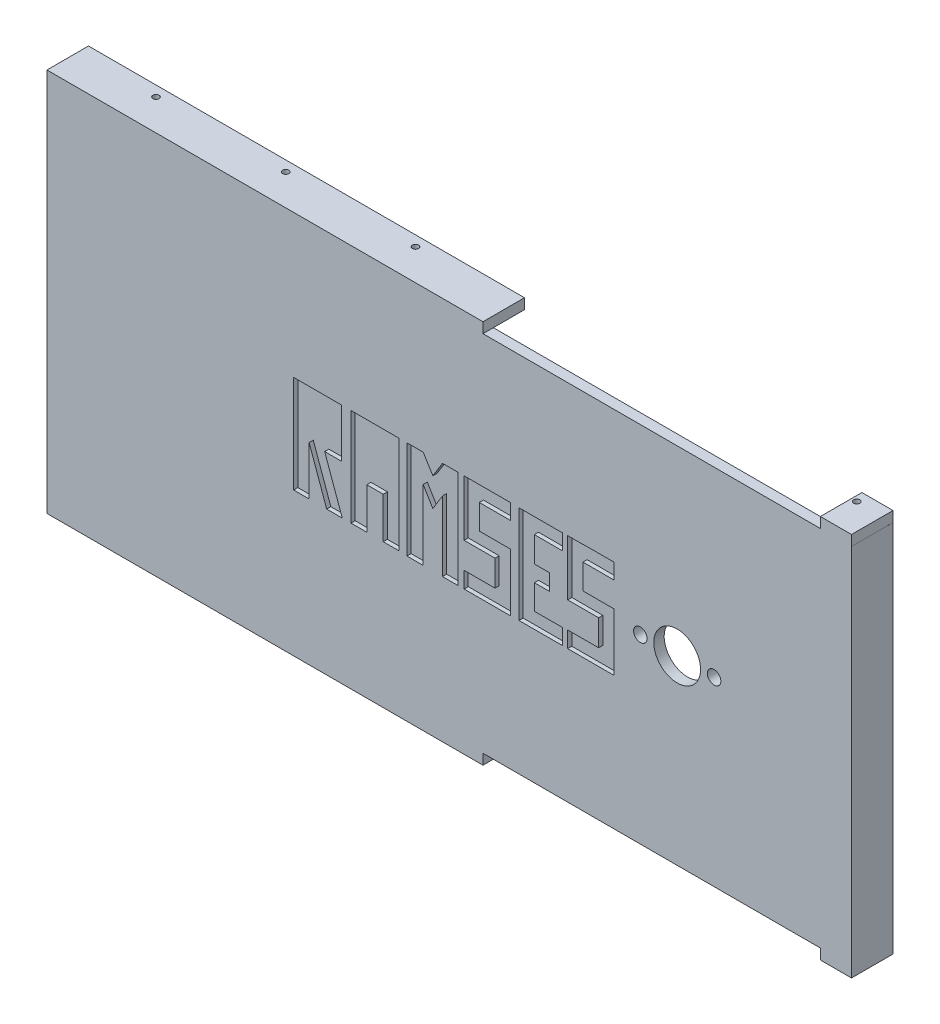
SolidWorks part; units mm, degrees
ref_plane "Front Plane" through (0, 0, 0) normal (0, 0, 1) x (1, 0, 0)
ref_plane "Top Plane" through (0, 0, 0) normal (0, 1, 0) x (1, 0, 0)
ref_plane "Right Plane" through (0, 0, 0) normal (1, 0, 0) x (0, 0, -1)
sketch "Sketch1" plane through (0, 0, 0) normal (0, 0, 1) x (1, 0, 0)
  line L1 (-191.77, 114.3) -> (191.77, 114.3)
  line L2 (-191.77, 114.3) -> (-191.77, -114.3)
  line L3 (-191.77, -114.3) -> (191.77, -114.3)
  line L4 (191.77, 114.3) -> (191.77, -114.3)
  line L5 (-191.77, 114.3) -> (191.77, -114.3) construction
  line L6 (-191.77, -114.3) -> (191.77, 114.3) construction
  point P1 (0, 0)
  dimension "D1" = 383.54
  dimension "D2" = 228.6
extrude "Boss-Extrude1" add sketch "Sketch1" along normal blind 5.08
ref_plane "Plane1" through (0, 0, 5.08) normal (0, 0, 1) x (1, 0, 0)
sketch "Sketch3" plane through (0, 0, 5.08) normal (0, 0, 1) x (1, 0, 0)
  line L0 (-20.7021, -23.9948) -> (-20.7021, 23.9948) construction
  line L5 (-76.1221, 23.9948) -> (76.1221, 23.9948)
  line L6 (-76.1221, 23.9948) -> (-76.1221, -23.9948)
  line L7 (-76.1221, -23.9948) -> (76.1221, -23.9948)
  line L8 (76.1221, 23.9948) -> (76.1221, -23.9948)
  line L9 (-76.1221, 23.9948) -> (76.1221, -23.9948) construction
  line L10 (-76.1221, -23.9948) -> (76.1221, 23.9948) construction
  line L17 (-20.7021, 23.9948) -> (4.3607, 23.9948) construction
  line L18 (4.3607, 23.9948) -> (4.3607, -23.9948) construction
  line L19 (4.3607, -23.9948) -> (29.9215, -23.9948) construction
  line L20 (29.9215, -23.9948) -> (29.9215, 23.9948) construction
  line L21 (-12.7351, 23.9948) -> (-8.0047, 16.3708)
  line L22 (-20.7021, 23.9948) -> (-12.7351, 23.9948)
  line L23 (-20.7021, 23.9948) -> (-20.7021, -23.9948)
  line L24 (-20.7021, -23.9948) -> (-12.7351, -23.9948)
  line L50 (-12.7351, 23.9948) -> (-12.7351, -23.9948)
  line L51 (4.3607, 23.9948) -> (-3.2743, 23.9948)
  line L64 (4.3607, 23.9948) -> (4.3607, -23.9948)
  line L65 (4.3607, -23.9948) -> (-3.2743, -23.9948)
  line L114 (-3.2743, 23.9948) -> (-3.2743, -23.9948)
  line L115 (-8.0047, 16.3708) -> (-3.2743, 23.9948)
  line L153 (-8.0047, 2.4263) -> (-3.2743, 10.2085)
  line L154 (-8.0047, 2.4263) -> (-12.7351, 10.3134)
  line L155 (-12.7351, 23.9948) -> (-3.2743, 23.9948) construction
  line L156 (-76.163, 24.0432) -> (-76.163, -23.7288) construction
  line L157 (-68.5707, 0.1572) -> (-60.9507, 0.1572)
  line L158 (-76.163, 24.0432) -> (-68.5707, 24.0432)
  line L159 (-76.163, 24.0432) -> (-76.163, -23.7288)
  line L160 (-76.163, -23.7288) -> (-68.5707, -23.7288)
  line L161 (-68.5707, 24.0432) -> (-68.5707, -23.7288)
  line L162 (-76.163, 24.0432) -> (-52.7715, 24.0432)
  line L163 (-76.163, 24.0432) -> (-76.163, 16.3708)
  line L164 (-76.163, 16.3708) -> (-52.7715, 16.3708)
  line L165 (-52.7715, 24.0432) -> (-52.7715, 16.3708)
  line L166 (-52.7715, 24.0432) -> (-60.1444, 24.0432)
  line L167 (-52.7715, 24.0432) -> (-52.7715, 7.9935)
  line L168 (-52.7715, 7.9935) -> (-60.1444, 7.9935)
  line L169 (-60.1444, 24.0432) -> (-60.1444, 7.9935)
  line L170 (-52.7715, 7.9935) -> (-76.163, 7.9935)
  line L171 (-52.7715, 7.9935) -> (-52.7715, 0.1572)
  line L172 (-52.7715, 0.1572) -> (-76.163, 0.1572)
  line L173 (-76.163, 7.9935) -> (-76.163, 0.1572)
  line L174 (-68.5707, 0.1572) -> (-59.9689, -23.7288)
  line L175 (-60.9507, 0.1572) -> (-52.3489, -23.7288)
  line L176 (-59.9689, -23.7288) -> (-52.3489, -23.7288)
  line L177 (-24.6254, 24.0432) -> (-24.6254, -23.7288)
  line L178 (-24.6254, 0.1572) -> (-24.6254, 24.0432)
  line L179 (-48.0899, -23.7288) -> (-48.0899, 24.0432) construction
  line L180 (-48.0899, 24.0432) -> (-40.3512, 24.0432)
  line L181 (-48.0899, 24.0432) -> (-48.0899, -23.7288)
  line L182 (-48.0899, -23.7288) -> (-40.3512, -23.7288)
  line L183 (-40.3512, 24.0432) -> (-40.3512, -23.7288)
  line L184 (-48.0899, 24.0432) -> (-24.6254, 24.0432)
  line L185 (-48.0899, 24.0432) -> (-48.0899, 16.3708)
  line L186 (-48.0899, 16.3708) -> (-24.6254, 16.3708)
  line L187 (-24.6254, 24.0432) -> (-24.6254, 16.3708)
  line L188 (-24.6254, 24.0432) -> (-32.2936, 24.0432)
  line L189 (-24.6254, 24.0432) -> (-24.6254, -23.7288)
  line L190 (-24.6254, -23.7288) -> (-32.2936, -23.7288)
  line L191 (-32.2936, 24.0432) -> (-32.2936, -23.7288)
  line L192 (-48.0899, 4.232) -> (-24.6254, 4.232)
  line L193 (-48.0899, 4.232) -> (-48.0899, -3.5926)
  line L194 (-48.0899, -3.5926) -> (-24.6254, -3.5926)
  line L195 (-24.6254, 4.232) -> (-24.6254, -3.5926)
  line L196 (34.1269, -23.8878) -> (34.1269, 23.8842) construction
  line L197 (34.1269, 23.8842) -> (41.6289, 23.8842)
  line L198 (34.1269, 23.8842) -> (34.1269, -23.8878)
  line L199 (34.1269, -23.8878) -> (41.6289, -23.8878)
  line L200 (41.6289, 23.8842) -> (41.6289, -23.8878)
  line L201 (34.1269, -23.8878) -> (55.4971, -23.8878)
  line L202 (34.1269, -23.8878) -> (34.1269, -16.2154)
  line L203 (34.1269, -16.2154) -> (55.4971, -16.2154)
  line L204 (55.4971, -23.8878) -> (55.4971, -16.2154)
  line L205 (34.1269, 23.8842) -> (55.4971, 23.8842)
  line L206 (34.1269, 23.8842) -> (34.1269, 16.2607)
  line L207 (34.1269, 16.2607) -> (55.4971, 16.2607)
  line L208 (55.4971, 23.8842) -> (55.4971, 16.2607)
  line L209 (34.1489, 3.8067) -> (49.109, 3.8067)
  line L210 (34.1489, 3.8067) -> (34.1489, -4.1154)
  line L211 (34.1489, -4.1154) -> (49.109, -4.1154)
  line L212 (49.109, 3.8067) -> (49.109, -4.1154)
  line L213 (34.1489, 3.8067) -> (49.109, -4.1154) construction
  line L214 (34.1489, -4.1154) -> (49.109, 3.8067) construction
  line L215 (-8.0047, 23.9948) -> (-8.0047, 3.39) construction
  line L216 (80.6118, -23.9098) -> (80.6118, 24.0798) construction
  line L217 (7.2667, 23.9948) -> (29.9215, 23.9948)
  line L218 (7.2667, 23.9948) -> (7.2667, 16.4151)
  line L219 (7.2667, 16.4151) -> (29.9215, 16.4151)
  line L220 (29.9215, 23.9948) -> (29.9215, 16.4151)
  line L221 (7.2667, 23.9948) -> (14.7134, 23.9948)
  line L222 (7.2667, 23.9948) -> (7.2667, -3.3398)
  line L223 (7.2667, -3.3398) -> (14.7134, -3.3398)
  line L224 (14.7134, 23.9948) -> (14.7134, -3.3398)
  line L225 (7.2667, -3.3398) -> (29.9215, -3.3398)
  line L226 (7.2667, -3.3398) -> (7.2667, 4.2802)
  line L227 (7.2667, 4.2802) -> (29.9215, 4.2802)
  line L228 (29.9215, -3.3398) -> (29.9215, 4.2802)
  line L229 (29.9215, 4.2802) -> (22.4125, 4.2802)
  line L230 (29.9215, 4.2802) -> (29.9215, -23.9948)
  line L231 (29.9215, -23.9948) -> (22.4125, -23.9948)
  line L232 (22.4125, 4.2802) -> (22.4125, -23.9948)
  line L233 (29.9215, -23.9948) -> (7.2667, -23.9948)
  line L234 (29.9215, -23.9948) -> (29.9215, -16.061)
  line L235 (29.9215, -16.061) -> (7.2667, -16.061)
  line L236 (7.2667, -23.9948) -> (7.2667, -16.061)
  line L237 (57.9571, 24.0798) -> (80.6118, 24.0798)
  line L238 (57.9571, 24.0798) -> (57.9571, 16.5001)
  line L239 (57.9571, 16.5001) -> (80.6118, 16.5001)
  line L240 (80.6118, 24.0798) -> (80.6118, 16.5001)
  line L241 (57.9571, 24.0798) -> (65.4037, 24.0798)
  line L242 (57.9571, 24.0798) -> (57.9571, -3.2485)
  line L243 (57.9571, -3.2485) -> (65.4037, -3.2485)
  line L244 (65.4037, 24.0798) -> (65.4037, -3.2485)
  line L245 (57.9571, -3.2485) -> (80.6118, -3.2485)
  line L246 (57.9571, -3.2485) -> (57.9571, 4.2802)
  line L247 (57.9571, 4.2802) -> (80.6118, 4.2802)
  line L248 (80.6118, -3.2485) -> (80.6118, 4.2802)
  line L249 (80.6118, 4.2802) -> (73.1028, 4.2802)
  line L250 (80.6118, 4.2802) -> (80.6118, -23.9098)
  line L251 (80.6118, -23.9098) -> (73.1028, -23.9098)
  line L252 (73.1028, 4.2802) -> (73.1028, -23.9098)
  line L253 (80.6118, -23.9098) -> (57.9571, -23.9098)
  line L254 (80.6118, -23.9098) -> (80.6118, -15.976)
  line L255 (80.6118, -15.976) -> (57.9571, -15.976)
  line L256 (57.9571, -23.9098) -> (57.9571, -15.976)
  point P0 (0, 0)
  point P157 (41.6289, -0.1544)
  dimension "D1" = 47.7719
  dimension "D2" = 7.62
  dimension "D3" = 7.9338
extrude "Cut-Extrude4" cut sketch "Sketch3" against normal blind 2.032 and the other way blind 2.54 contours L6 L164 L161 L5 | L169 L5 L161 L164 | L5 L169 L164 L165 | L164 L169 L168 L167 | L172 L161 L170 L6 | L161 L172 L6 L160 | L170 L161 L164 L6 | L170 L169 L164 L161 | L172 L171 L168 L170 L161 L157 | L174 L176 L175 L157 | L181 L186 L183 L5 | L191 L5 L183 L186 | L5 L191 L186 L177 | L191 L192 L178 L186 | L183 L192 L191 L186 | L181 L192 L183 L186 | L181 L194 L183 L192 | L183 L194 L191 L192 | L191 L194 L177 L189 L192 | L194 L181 L182 L183 | L194 L191 L190 L189 | L50 L5 L23 L7 | L154 L153 L114 L115 L21 L50 | L5 L114 L7 L64 | L217 L224 L219 L220 | L224 L5 L218 L219 | L208 L205 L200 L207 | L222 L227 L224 L219 | L227 L222 L223 L224 | L232 L227 L224 L225 | L227 L232 L225 L228 | L235 L230 L225 L232 | L230 L235 L232 L7 | L236 L7 L232 L235 | L198 L207 L200 L197 | L211 L210 L209 L200 L207 L198 L203 | L210 L211 L200 L209 | L212 L209 L200 L211 | L203 L198 L199 L200 | L201 L204 L203 L200 | L242 L247 L244 L239 | L244 L5 L238 L239 | L5 L244 L239 L8 | L237 L244 L5 L8 L239 L240 | L247 L242 L243 L244 | L256 L253 L252 L255 | L252 L247 L244 L245 | L247 L252 L245 L8 | L245 L248 L247 L8 | L255 L250 L245 L8 | L255 L8 L245 L252 | L8 L255 L252 L251 | L250 L255 L8 L251
sketch "Sketch4" plane through (0, 0, 5.08) normal (0, 0, 1) x (1, 0, 0)
  line L0 (-191.77, 0) -> (191.77, 0) construction
  line L1 (-191.77, 114.3) -> (-191.77, -114.3) construction
  line L2 (191.77, -114.3) -> (191.77, 114.3) construction
  line L3 (191.77, 0) -> (191.77, 88.8363) construction
  line L4 (191.77, 88.8363) -> (191.77, -88.9637) construction
  line L5 (191.77, -88.9637) -> (-191.77, -88.9637) construction
  line L6 (-191.77, -88.9637) -> (-191.77, 88.8363) construction
  line L7 (-191.77, 88.8363) -> (191.77, 88.8363) construction
  line L9 (-191.77, 114.3) -> (191.77, 114.3)
  line L10 (-191.77, 114.3) -> (-191.77, 88.8363)
  line L11 (-191.77, 88.8363) -> (191.77, 88.8363)
  line L12 (191.77, 114.3) -> (191.77, 88.8363)
  line L13 (-191.77, -88.9637) -> (191.77, -88.9637)
  line L14 (-191.77, -88.9637) -> (-191.77, -114.3)
  line L15 (-191.77, -114.3) -> (191.77, -114.3)
  line L16 (191.77, -88.9637) -> (191.77, -114.3)
extrude "Cut-Extrude5" cut sketch "Sketch4" against normal blind 6.35
sketch "Sketch7" plane through (0, 0, 5.08) normal (0, 0, 1) x (1, 0, 0)
  line L4 (96.8088, -0.234) -> (100.1108, -0.234)
  line L6 (122.9708, -0.234) -> (126.2728, -0.234)
  circle A0 centre (93.5068, -0.234) radius 3.302
  circle A1 centre (111.5408, -0.234) radius 11.43
  circle A2 centre (129.6045, -0.234) radius 3.302
  dimension "D1" = 11.43
  dimension "D4" = 6.604
  dimension "D5" = 6.604
  dimension "D2" = 3.302
  dimension "D3" = 3.302
extrude "Cut-Extrude6" cut sketch "Sketch7" against normal blind 203.2
sketch "Sketch8" plane through (0, 0, 5.08) normal (0, 0, 1) x (1, 0, 0)
  line L0 (-191.77, 88.8363) -> (191.77, 88.8363) construction
  line L1 (-196.85, 93.9163) -> (196.85, 93.9163)
  line L2 (-196.85, 93.9163) -> (-196.85, -94.0437)
  line L3 (-196.85, -94.0437) -> (196.85, -94.0437)
  line L4 (196.85, 93.9163) -> (196.85, -94.0437)
  line L5 (191.77, -88.9637) -> (191.77, 88.8363) construction
  line L6 (191.77, -88.9637) -> (-191.77, -88.9637) construction
  line L7 (-191.77, 88.8363) -> (-191.77, -88.9637) construction
  line L8 (16.51, 88.8363) -> (191.77, 88.8363)
  line L9 (191.77, 93.9163) -> (196.85, 93.9163)
  line L10 (191.77, 93.9163) -> (191.77, 88.8358)
  line L11 (191.77, 88.8358) -> (196.85, 88.8358)
  line L12 (196.85, 93.9163) -> (196.85, 88.8358)
  line L13 (191.77, 88.8363) -> (196.85, 88.8363)
  line L14 (191.77, 88.8363) -> (191.77, 76.1363)
  line L15 (191.77, 76.1363) -> (196.85, 76.1363)
  line L16 (196.85, 88.8363) -> (196.85, 76.1363)
  line L17 (181.61, -88.9637) -> (196.85, -88.9637)
  line L18 (181.61, -88.9637) -> (181.61, -94.0437)
  line L19 (181.61, -94.0437) -> (196.85, -94.0437)
  line L20 (196.85, -88.9637) -> (196.85, -94.0437)
  line L21 (196.85, -88.9637) -> (191.77, -88.9637)
  line L22 (196.85, -88.9637) -> (196.85, -76.2637)
  line L23 (196.85, -76.2637) -> (191.77, -76.2637)
  line L24 (191.77, -88.9637) -> (191.77, -76.2637)
  line L25 (16.51, 88.8363) -> (-196.85, 88.8363)
  line L26 (16.51, 88.8363) -> (16.51, 93.9163)
  line L27 (16.51, 93.9163) -> (-196.85, 93.9163)
  line L28 (-196.85, 88.8363) -> (-196.85, 93.9163)
  line L29 (16.51, -88.9637) -> (-196.85, -88.9637)
  line L30 (16.51, -88.9637) -> (16.51, -94.0437)
  line L31 (16.51, -94.0437) -> (-196.85, -94.0437)
  line L32 (-196.85, -88.9637) -> (-196.85, -94.0437)
  line L33 (-196.85, 88.8363) -> (-191.77, 88.8363)
  line L34 (-196.85, 88.8363) -> (-196.85, -88.9637)
  line L35 (-196.85, -88.9637) -> (-191.77, -88.9637)
  line L36 (-191.77, 88.8363) -> (-191.77, -88.9637)
  line L37 (191.77, 76.1363) -> (191.77, -76.2637)
  line L38 (191.77, 88.8363) -> (181.61, 88.8363)
  line L39 (191.77, 88.8363) -> (191.77, 93.9163)
  line L40 (191.77, 93.9163) -> (181.61, 93.9163)
  line L41 (181.61, 88.8363) -> (181.61, 93.9163)
  point P37 (181.61, -91.5037)
  point P38 (16.51, -91.5037)
  point P39 (181.61, 91.3763)
  dimension "D1" = 5.08
  dimension "D2" = 5.08
  dimension "D3" = 5.08
  dimension "D4" = 5.08
  dimension "D5" = 10.16
  dimension "D6" = 15.24
  dimension "D7" = 17.78
  dimension "D8" = 12.7
  dimension "D9" = 165.1
  dimension "D10" = 165.1
extrude "Boss-Extrude2" add sketch "Sketch8" against normal blind 20.32 contours L14 L13 L4 L1 L10 L11 | L14 L15 L4 L11 | L24 L17 L4 L23 | L17 L18 L3 L4 | L30 L29 L2 L3 | L36 L25 L2 L29 | L25 L26 L1 L2 | L41 L8 L10 L1 | L15 L37 L23 L4
sketch "Sketch11" plane through (0, -94.0437, 0) normal (0, -1, 0) x (1, 0, 0)
  line L0 (-191.77, -10.16) -> (191.77, -10.16) construction
  line L4 (-196.85, 5.08) -> (16.51, 5.08) construction
  line L5 (196.85, -15.24) -> (196.85, 5.08) construction
  line L6 (-191.77, 5.08) -> (-191.77, -15.24) construction
  circle A0 centre (-158.75, -10.16) radius 1.5
  circle A1 centre (-95.25, -10.16) radius 1.5
  circle A2 centre (184.15, -10.16) radius 1.5
  circle A3 centre (-31.75, -10.16) radius 1.5
  dimension "D2" = 12.7
  dimension "D1" = 15.24
  dimension "D3" = 215.9
  dimension "D4" = 63.5
  dimension "D5" = 63.5
extrude "Cut-Extrude7" cut sketch "Sketch11" against normal blind 381
